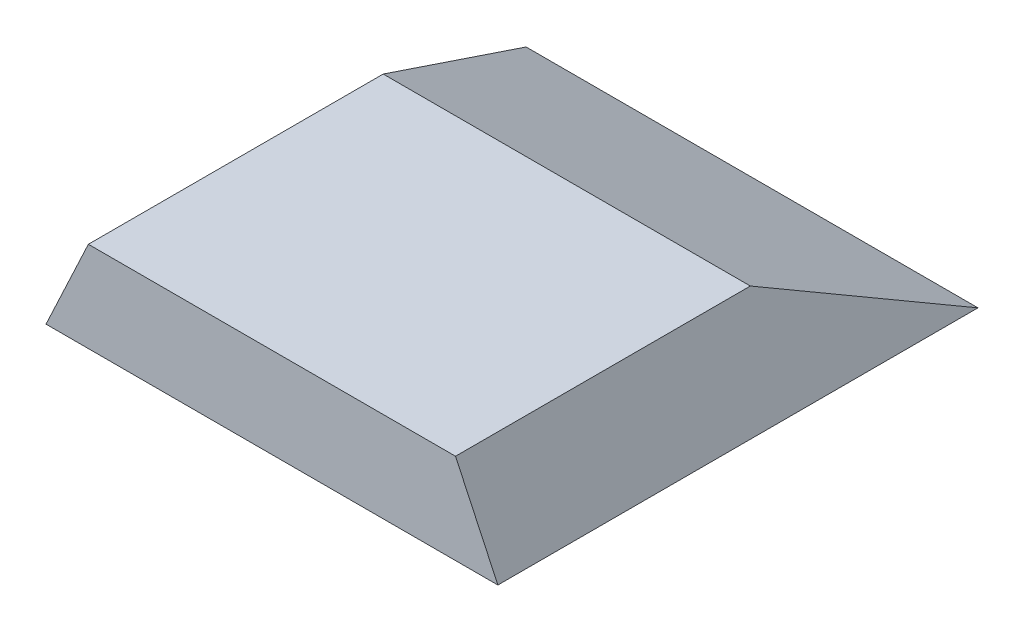
SolidWorks part; units mm, degrees
ref_plane "Front Plane" through (0, 0, 0) normal (0, 0, 1) x (1, 0, 0)
ref_plane "Top Plane" through (0, 0, 0) normal (0, 1, 0) x (1, 0, 0)
ref_plane "Right Plane" through (0, 0, 0) normal (1, 0, 0) x (0, 0, -1)
sketch "Sketch1" plane through (0, 0, 0) normal (0, 0, 1) x (1, 0, 0)
  line L0 (0, 14.8611) -> (0, -8.4611) construction
  line L9 (-6.5, 3.2) -> (-8, 0)
  line L10 (-8, 0) -> (8, 0)
  line L11 (8, 0) -> (6.5, 3.2)
  line L12 (6.5, 3.2) -> (-6.5, 3.2)
  point P4 (0, 0)
  point P10 (0, 3.2)
  dimension "D1" = 13
  dimension "D2" = 16
  dimension "D3" = 3.2
extrude "Boss-Extrude1" add sketch "Sketch1" along normal blind 17
sketch "Sketch2" plane through (0, 0, 0) normal (1, 0, 0) x (0, 0, -1)
  line L0 (0, 0) -> (-6.561, 3.2)
  line L1 (-17, 3.2) -> (0, 3.2) construction
  line L2 (-17, 0) -> (0, 0) construction
  line L3 (-6.561, 3.2) -> (0, 3.2)
  line L4 (0, 3.2) -> (0, 0)
  dimension "D1" = 26
extrude "Cut-Extrude1" cut sketch "Sketch2" against normal through all both and the other way through all
